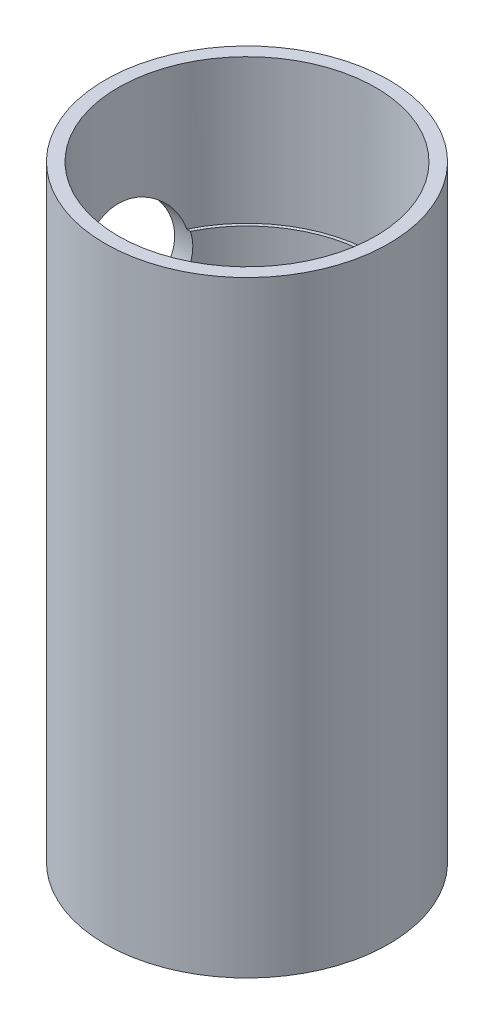
SolidWorks part; units mm, degrees
ref_plane "Front Plane" through (0, 0, 0) normal (0, 0, 1) x (1, 0, 0)
ref_plane "Top Plane" through (0, 0, 0) normal (0, 1, 0) x (1, 0, 0)
ref_plane "Right Plane" through (0, 0, 0) normal (1, 0, 0) x (0, 0, -1)
sketch "Sketch1" plane through (0, 0, 0) normal (0, 1, 0) x (1, 0, 0)
  line L0 (0, 38.25) -> (0, 43.25) construction
  circle A0 centre (0, 0) radius 38.25
  circle A1 centre (0, 0) radius 43.25
  dimension "D1" = 76.5
  dimension "D2" = 5
extrude "Boss-Extrude1" add sketch "Sketch1" along normal mid plane 185
sketch "Sketch2" plane through (0, -92.5, 0) normal (0, -1, 0) x (1, 0, 0)
  line L0 (0, 36.25) -> (0, 38.25) construction
  circle A0 centre (0, 0) radius 36.25
  circle A1 centre (0, 0) radius 38.25 construction
  circle A2 centre (0, 0) radius 38.25
  dimension "D1" = 2
extrude "Boss-Extrude2" add sketch "Sketch2" against normal blind 100 from offset 6.35 offset against normal yes
sketch "Sketch6" plane through (0, 92.5, 0) normal (0, 1, 0) x (1, 0, 0)
  line L0 (0, 38.25) -> (0, 39.25) construction
  circle A0 centre (0, 0) radius 39.25
  circle A1 centre (0, 0) radius 38.25 construction
  circle A2 centre (0, 0) radius 38.25
  dimension "D1" = 1
extrude "Cut-Extrude3" cut sketch "Sketch6" against normal blind 44
sketch "Sketch7" plane through (0, 0, 0) normal (1, 0, 0) x (0, 0, -1)
  line L0 (43.25, 92.5) -> (-43.25, 92.5) construction
  circle A0 centre (0, 44.35) radius 17.5
  dimension "D2" = 35
  dimension "D1" = 48.15
extrude "Cut-Extrude4" cut sketch "Sketch7" against normal through all
